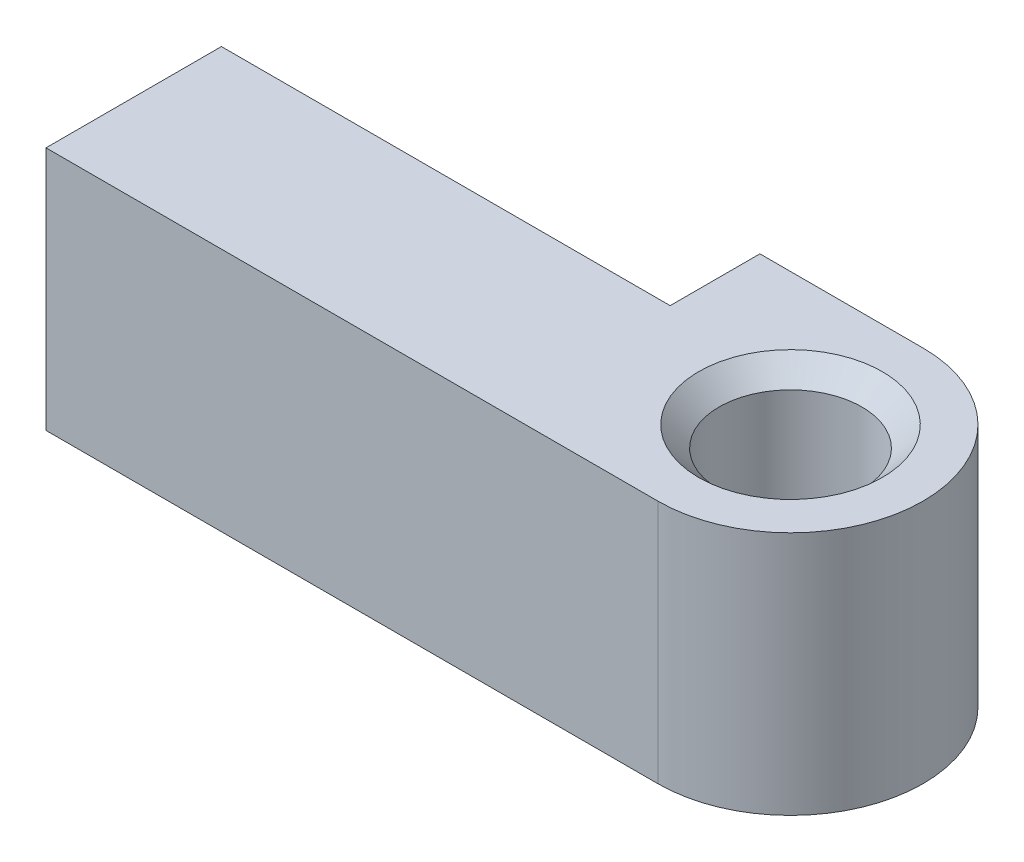
SolidWorks part; units mm, degrees
ref_plane "Front Plane" through (0, 0, 0) normal (0, 0, 1) x (1, 0, 0)
ref_plane "Top Plane" through (0, 0, 0) normal (0, 1, 0) x (1, 0, 0)
ref_plane "Right Plane" through (0, 0, 0) normal (1, 0, 0) x (0, 0, -1)
sketch "Sketch2" plane through (0, 0, 0) normal (0, 1, 0) x (1, 0, 0)
  line L1 (11, 2.2) -> (15, 2.2)
  line L2 (0, 0) -> (0, -4.3)
  line L3 (0, -4.3) -> (15, -4.3)
  line L7 (0, 0) -> (11, 0)
  line L8 (11, 2.2) -> (11, 0)
  arc A0 (15, -4.3) -> (15, 2.2) centre (15, -1.05) ccw
  circle A1 centre (15, -1.05) radius 1.75
  dimension "D5" = 3.5
  dimension "D1" = 6.5
  dimension "D2" = 15
  dimension "D3" = 11
  dimension "D4" = 2.2
extrude "Boss-Extrude1" add sketch "Sketch2" along normal blind 6
chamfer "Chamfer1" distance 0.5 angle 45 1 edges at (15, 6, 2.8)
